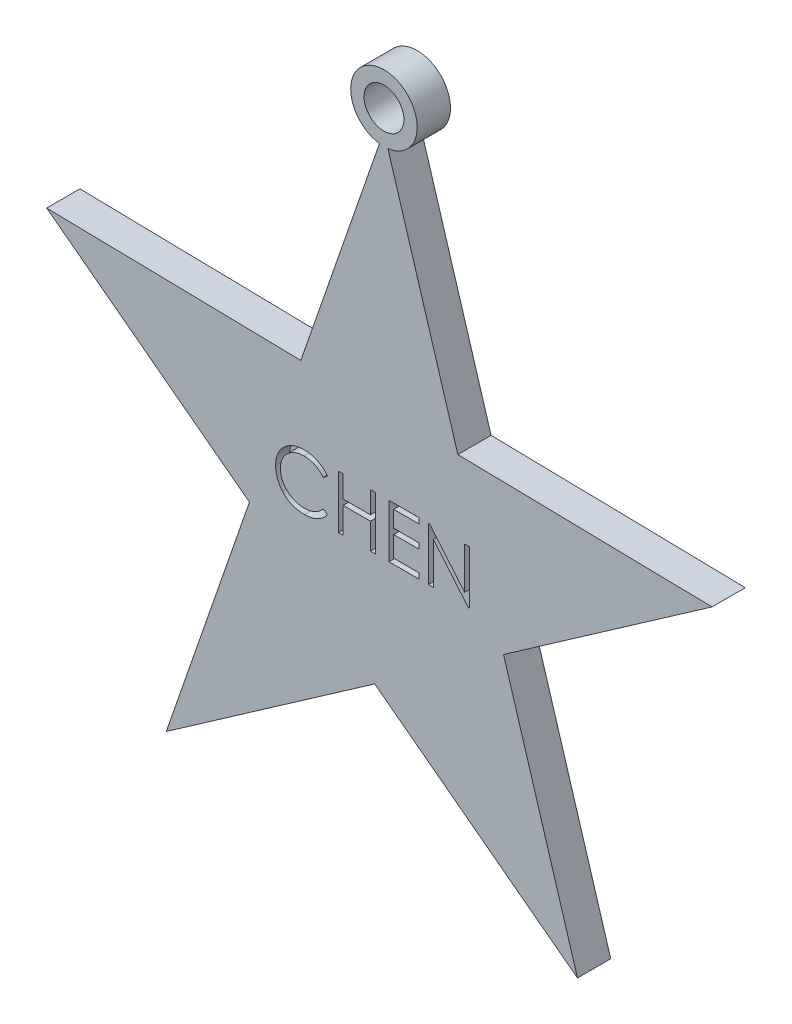
SolidWorks part; units mm, degrees
ref_plane "前视基准面" through (0, 0, 0) normal (0, 0, 1) x (1, 0, 0)
ref_plane "上视基准面" through (0, 0, 0) normal (0, 1, 0) x (1, 0, 0)
ref_plane "右视基准面" through (0, 0, 0) normal (1, 0, 0) x (0, 0, -1)
sketch "草图1" plane through (0, 0, 0) normal (0, 0, 1) x (1, 0, 0)
  line L0 (-24.8444, 8.6019) -> (-9.6086, -2.9198)
  line L6 (15.0434, -21.5623) -> (9.4879, -3.2869)
  line L7 (0.1623, 25.3009) -> (-5.7461, 8.2361)
  line L8 (-15.8583, -20.9703) -> (-0.1924, -10.0406)
  line L9 (25.1556, 7.6441) -> (6.0538, 8.01)
  line L10 (-5.7461, 8.2361) -> (-24.8444, 8.6019)
  line L11 (-9.6086, -2.9198) -> (-15.8583, -20.9703)
  line L12 (-0.1924, -10.0406) -> (15.0434, -21.5623)
  line L13 (9.4879, -3.2869) -> (25.1556, 7.6441)
  line L14 (6.0538, 8.01) -> (0.7991, 25.2958)
  circle A0 centre (0.5006, 27.7779) radius 1.5
  arc A1 (0.7991, 25.2958) -> (0.1623, 25.3009) centre (0.5006, 27.7779) ccw
  point P4 (-48.0492, -5.3216)
  point P9 (0.5006, 28.7999)
  point P10 (0.5006, 28.0188)
extrude "凸台-拉伸1" add sketch "草图1" along normal blind 2.5 contours L13 L9 L14 A1 L7 L10 L0 L11 L8 L12 L6
sketch "草图2" plane through (0, 0, 2.5) normal (0, 0, 1) x (1, 0, 0)
  text T0 "CHEN" font "Century Gothic" height 4
extrude "切除-拉伸1" cut sketch "草图2" against normal blind 1
sketch "草图4" plane through (0, 0, 2.5) normal (0, 0, 1) x (1, 0, 0)
  circle A0 centre (0.5006, 27.7779) radius 1.5
  arc A1 (0.7991, 25.2958) -> (0.1623, 25.3009) centre (0.5006, 27.7779) ccw construction
extrude "切除-拉伸3" cut sketch "草图4" against normal blind 2.5
